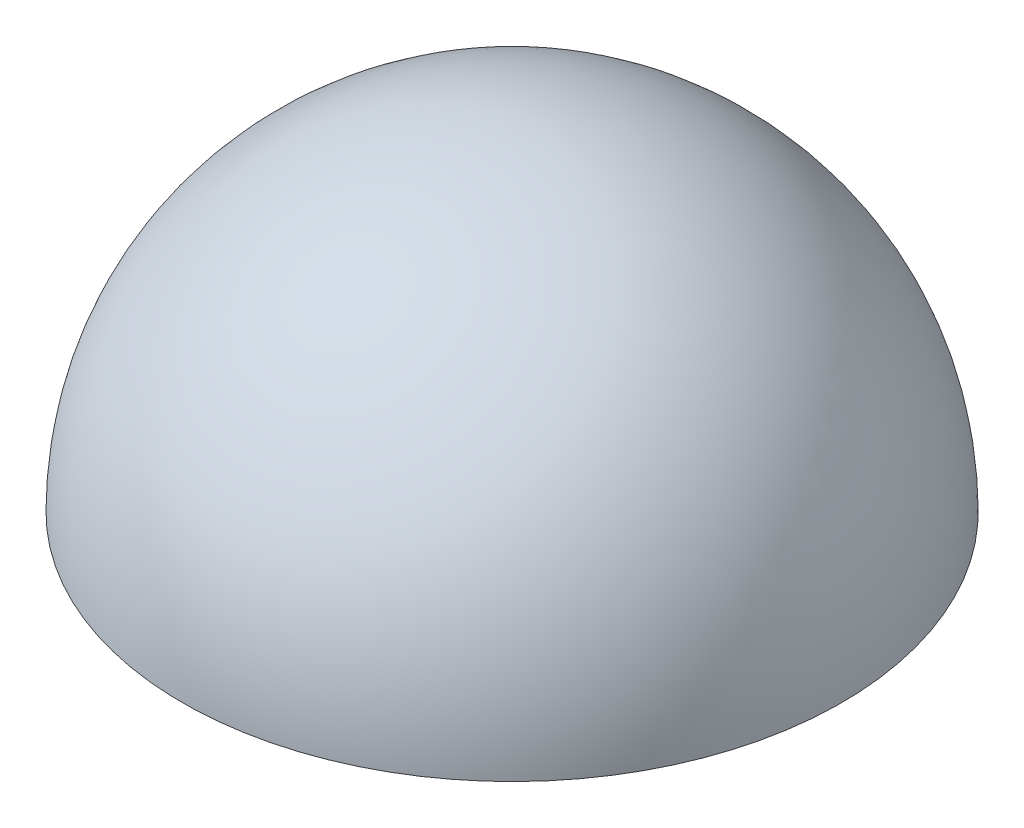
SolidWorks part; units mm, degrees
ref_plane "前视基准面" through (0, 0, 0) normal (0, 0, 1) x (1, 0, 0)
ref_plane "上视基准面" through (0, 0, 0) normal (0, 1, 0) x (1, 0, 0)
ref_plane "右视基准面" through (0, 0, 0) normal (1, 0, 0) x (0, 0, -1)
sketch "草图1" plane through (0, 0, 0) normal (0, 1, 0) x (1, 0, 0)
  line L0 (0, 0) -> (0, -94)
  arc A0 (0, 0) -> (0, -94) centre (0, -47) cw
revolve "旋转1" add sketch "草图1" angle 180 about L0
shell "抽壳3" thickness 1
